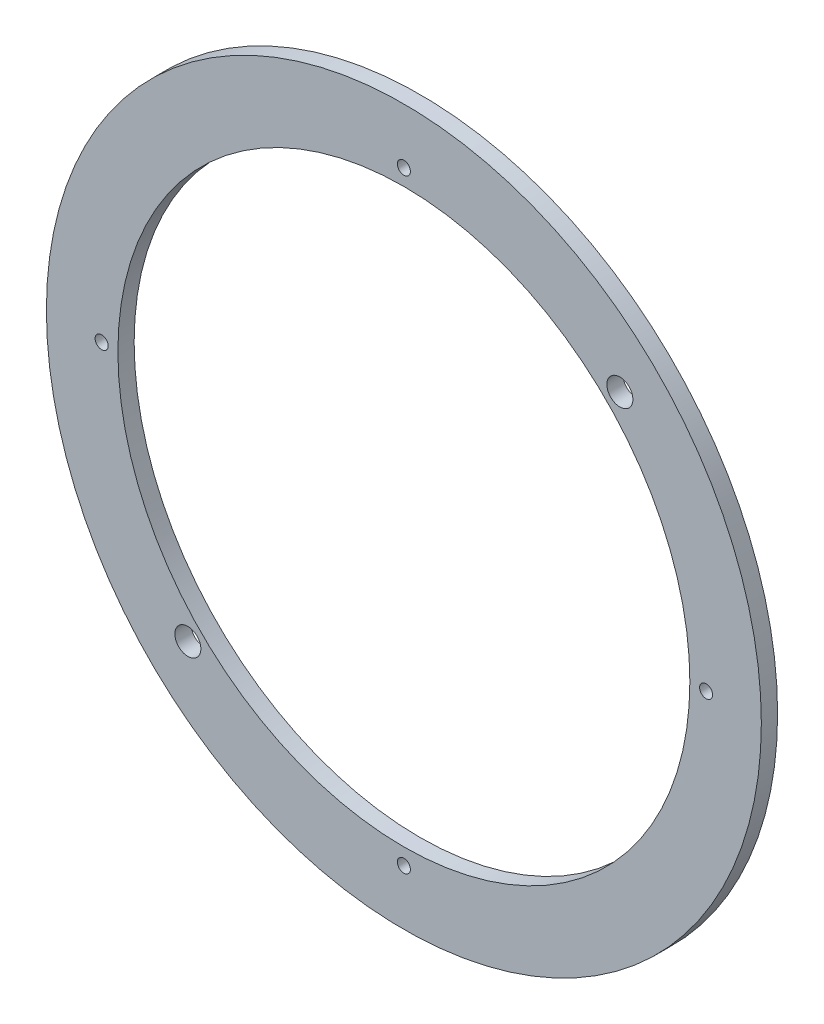
SolidWorks part; units mm, degrees
ref_plane "Front Plane" through (0, 0, 0) normal (0, 0, 1) x (1, 0, 0)
ref_plane "Top Plane" through (0, 0, 0) normal (0, 1, 0) x (1, 0, 0)
ref_plane "Right Plane" through (0, 0, 0) normal (1, 0, 0) x (0, 0, -1)
sketch "Sketch1" plane through (0, 0, 0) normal (0, 0, 1) x (1, 0, 0)
  line L0 (-78.3987, -3.3654) -> (61.3013, -3.3654) construction
  line L1 (-5.8227, 60.5836) -> (-5.8227, 59.1774)
  line L2 (-57.9401, 46.026) -> (40.8427, -52.7569) construction
  line L3 (40.8427, 46.026) -> (-57.9401, -52.7569) construction
  line L4 (-13.4427, 60.5073) -> (-13.4427, 59.1774)
  line L5 (-13.4427, 59.1774) -> (-5.8227, 59.1774)
  line L12 (2.7798, 58.212) -> (10.1401, 56.2398)
  line L13 (10.5041, 57.5981) -> (10.1401, 56.2398)
  line L14 (3.124, 59.4967) -> (2.7798, 58.212)
  line L18 (18.1997, 53.0809) -> (24.7988, 49.2709)
  line L19 (25.5019, 50.4887) -> (24.7988, 49.2709)
  line L20 (18.8647, 54.2327) -> (18.1997, 53.0809)
  line L24 (31.7661, 44.1336) -> (37.1543, 38.7454)
  line L25 (38.1486, 39.7398) -> (37.1543, 38.7454)
  line L26 (32.7065, 45.074) -> (31.7661, 44.1336)
  line L30 (42.5546, 31.9799) -> (46.3646, 25.3808)
  line L31 (47.5824, 26.0839) -> (46.3646, 25.3808)
  line L32 (43.7063, 32.6449) -> (42.5546, 31.9799)
  line L36 (49.8298, 17.4482) -> (51.802, 10.0878)
  line L37 (53.1603, 10.4518) -> (51.802, 10.0878)
  line L38 (51.1145, 17.7924) -> (49.8298, 17.4482)
  line L42 (53.0961, 1.5286) -> (53.0961, -6.0914)
  line L43 (54.5023, -6.0914) -> (53.0961, -6.0914)
  line L44 (54.426, 1.5286) -> (53.0961, 1.5286)
  line L48 (52.1307, -14.6939) -> (50.1585, -22.0543)
  line L49 (51.5168, -22.4183) -> (50.1585, -22.0543)
  line L50 (53.4154, -15.0382) -> (52.1307, -14.6939)
  line L54 (46.9996, -30.1138) -> (43.1896, -36.713)
  line L55 (44.4074, -37.4161) -> (43.1896, -36.713)
  line L56 (48.1513, -30.7788) -> (46.9996, -30.1138)
  line L60 (38.0523, -43.6803) -> (32.6641, -49.0684)
  line L61 (33.6585, -50.0628) -> (32.6641, -49.0684)
  line L62 (38.9927, -44.6207) -> (38.0523, -43.6803)
  line L66 (25.8986, -54.4687) -> (19.2995, -58.2787)
  line L67 (20.0026, -59.4965) -> (19.2995, -58.2787)
  line L68 (26.5636, -55.6205) -> (25.8986, -54.4687)
  line L72 (11.3669, -61.744) -> (4.0065, -63.7162)
  line L73 (4.3705, -65.0745) -> (4.0065, -63.7162)
  line L74 (11.7111, -63.0286) -> (11.3669, -61.744)
  line L78 (-4.5527, -65.0102) -> (-12.1727, -65.0102)
  line L79 (-12.1727, -66.4164) -> (-12.1727, -65.0102)
  line L80 (-4.5527, -66.3402) -> (-4.5527, -65.0102)
  line L84 (-20.7752, -64.0449) -> (-28.1356, -62.0727)
  line L85 (-28.4996, -63.431) -> (-28.1356, -62.0727)
  line L86 (-21.1195, -65.3295) -> (-20.7752, -64.0449)
  line L90 (-36.1951, -58.9137) -> (-42.7943, -55.1037)
  line L91 (-43.4974, -56.3215) -> (-42.7943, -55.1037)
  line L92 (-36.8601, -60.0655) -> (-36.1951, -58.9137)
  line L96 (-49.7616, -49.9665) -> (-55.1497, -44.5783)
  line L97 (-56.1441, -45.5726) -> (-55.1497, -44.5783)
  line L98 (-50.702, -50.9069) -> (-49.7616, -49.9665)
  line L102 (-60.55, -37.8128) -> (-64.36, -31.2137)
  line L103 (-65.5778, -31.9168) -> (-64.36, -31.2137)
  line L104 (-61.7018, -38.4778) -> (-60.55, -37.8128)
  line L109 (-71.1558, -16.2846) -> (-69.7975, -15.9207)
  line L110 (-69.1099, -23.6252) -> (-67.8253, -23.281)
  line L114 (-71.0915, -7.3614) -> (-71.0915, 0.2586)
  line L115 (-72.4977, 0.2586) -> (-71.0915, 0.2586)
  line L116 (-72.4215, -7.3614) -> (-71.0915, -7.3614)
  line L120 (-70.1262, 8.8611) -> (-68.154, 16.2214)
  line L121 (-69.5123, 16.5854) -> (-68.154, 16.2214)
  line L122 (-71.4108, 9.2053) -> (-70.1262, 8.8611)
  line L126 (-64.995, 24.281) -> (-61.185, 30.8801)
  line L127 (-62.4028, 31.5832) -> (-61.185, 30.8801)
  line L128 (-66.1468, 24.946) -> (-64.995, 24.281)
  line L132 (-56.0478, 37.8474) -> (-50.6596, 43.2356)
  line L133 (-51.6539, 44.2299) -> (-50.6596, 43.2356)
  line L134 (-56.9882, 38.7878) -> (-56.0478, 37.8474)
  line L138 (-43.8941, 48.6359) -> (-37.295, 52.4459)
  line L139 (-37.9981, 53.6637) -> (-37.295, 52.4459)
  line L140 (-44.5591, 49.7877) -> (-43.8941, 48.6359)
  line L144 (-29.3623, 55.9111) -> (-22.002, 57.8833)
  line L145 (-22.3659, 59.2416) -> (-22.002, 57.8833)
  line L146 (-29.7065, 57.1958) -> (-29.3623, 55.9111)
  line L147 (-8.9977, -2.9164) -> (-5.8227, 59.1774) construction
  line L148 (-8.9977, -2.9164) -> (10.1401, 56.2398) construction
  line L170 (-67.8253, -23.281) -> (-69.7975, -15.9207) [skipped]
  circle A0 centre (-8.5487, -3.3654) radius 55.88
  circle A1 centre (-8.5487, -3.3654) radius 69.85
  dimension "D1" = 111.76
  dimension "D2" = 139.7
  dimension "D4" = 7.62
  dimension "D5" = 24
  dimension "D6" = 15
extrude "Boss-Extrude1" add sketch "Sketch1" along normal blind 3.175
sketch "Sketch4" plane through (0, 0, 0) normal (0, 0, -1) x (-1, 0, 0)
  line L0 (8.5487, 52.5146) -> (8.5487, -59.2454) construction
  line L1 (-47.3313, -3.3654) -> (64.4287, -3.3654) construction
  line L2 (8.5487, -3.3654) -> (81.6471, -76.4638) construction
  line L3 (8.5487, -3.3654) -> (-56.7065, 61.8898) construction
  circle A0 centre (8.5487, -3.3654) radius 55.88 construction
  circle A1 centre (8.5487, -3.3654) radius 59.055
  circle A2 centre (8.5487, 55.6896) radius 1.27
  circle A3 centre (8.5487, -62.4204) radius 1.27
  circle A4 centre (-50.5063, -3.3654) radius 1.27
  circle A5 centre (67.6037, -3.3654) radius 1.27
  circle A6 centre (8.5487, -3.3654) radius 62.23
  circle A7 centre (-33.6585, 38.8418) radius 2.54
  circle A8 centre (50.7559, -45.5726) radius 2.54
  dimension "D1" = 118.11
  dimension "D2" = 2.54
  dimension "D3" = 2.54
  dimension "D4" = 2.54
  dimension "D5" = 2.54
  dimension "D8" = 124.46
  dimension "D9" = 5.08
  dimension "D10" = 5.08
  dimension "D6" = 45
  dimension "D7" = 45
extrude "Cut-Extrude2" cut sketch "Sketch4" against normal through all contours A1 A2 | A1 A2 | A1 A4 | A1 A4 | A1 A3 | A1 A3 | A1 A5 | A1 A5 | A1 A7 | A1 A7 | A1 A8 | A1 A8
